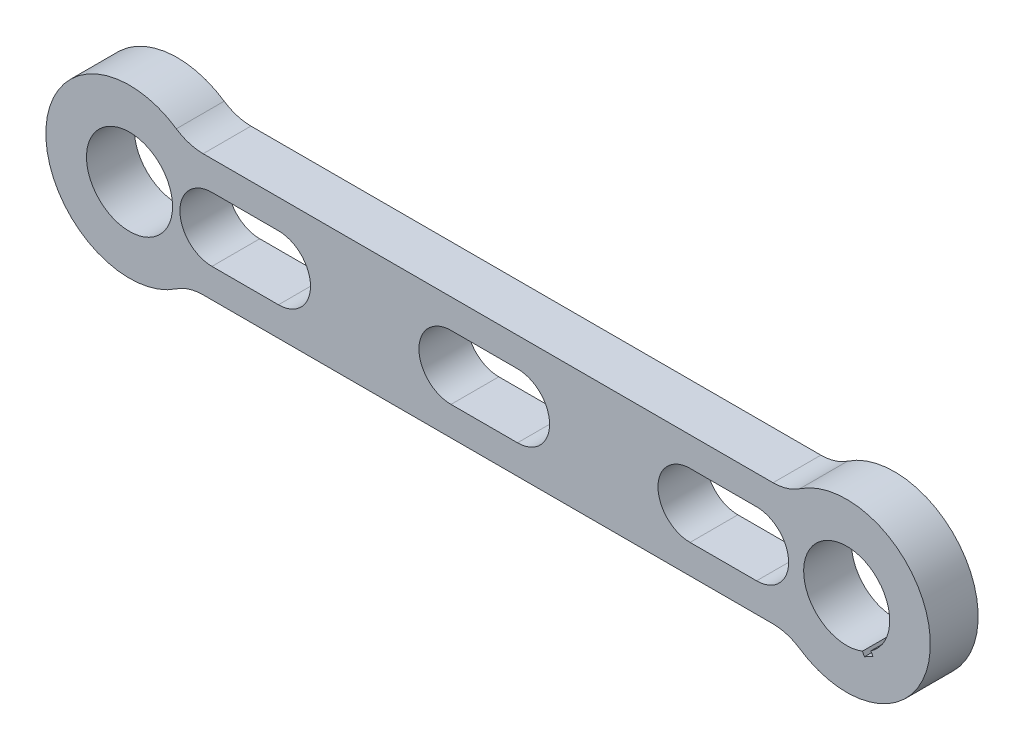
SolidWorks part; units mm, degrees
ref_plane "Front Plane" through (0, 0, 0) normal (0, 0, 1) x (1, 0, 0)
ref_plane "Top Plane" through (0, 0, 0) normal (0, 1, 0) x (1, 0, 0)
ref_plane "Right Plane" through (0, 0, 0) normal (1, 0, 0) x (0, 0, -1)
sketch "Sketch1" plane through (0, 0, 0) normal (0, 0, 1) x (1, 0, 0)
  line L0 (-70.6553, 0) -> (79.3447, 0) construction
  line L1 (55, 0) -> (-55, 0) construction
  line L2 (-53.413, 0) -> (-39.5014, 0) construction
  line L3 (-58.704, 12.7835) -> (67.3934, 12.7835)
  line L4 (-58.704, -12.7835) -> (67.3934, -12.7835)
  line L5 (-53.413, 6.7024) -> (-39.5014, 6.7024)
  line L6 (-53.413, -6.7024) -> (-39.5014, -6.7024)
  line L7 (-3.413, 0) -> (10.4986, 0) construction
  line L8 (-3.413, 6.7024) -> (10.4986, 6.7024)
  line L9 (-3.413, -6.7024) -> (10.4986, -6.7024)
  line L10 (46.587, 0) -> (60.4986, 0) construction
  line L11 (46.587, 6.7024) -> (60.4986, 6.7024)
  line L12 (46.587, -6.7024) -> (60.4986, -6.7024)
  arc A2 (-53.413, 6.7024) -> (-53.413, -6.7024) centre (-53.413, 0) ccw
  arc A3 (-39.5014, -6.7024) -> (-39.5014, 6.7024) centre (-39.5014, 0) ccw
  arc A4 (-3.413, 6.7024) -> (-3.413, -6.7024) centre (-3.413, 0) ccw
  arc A5 (10.4986, -6.7024) -> (10.4986, 6.7024) centre (10.4986, 0) ccw
  arc A6 (46.587, 6.7024) -> (46.587, -6.7024) centre (46.587, 0) ccw
  arc A7 (60.4986, -6.7024) -> (60.4986, 6.7024) centre (60.4986, 0) ccw
  arc A8 (-58.704, 12.7835) -> (-58.704, -12.7835) centre (-70.6553, 0) ccw
  arc A9 (67.3934, -12.7835) -> (67.3934, 12.7835) centre (79.3447, 0) ccw
  circle A10 centre (-70.6553, 0) radius 9
  circle A11 centre (79.3447, 0) radius 9
  point P7 (4.3447, 0)
  point P12 (-46.4572, 0)
  point P20 (3.5428, 0)
  point P27 (53.5428, 0)
  dimension "D2" = 18
  dimension "D1" = 3
extrude "Boss-Extrude3" add sketch "Sketch1" along normal blind 10
fillet "Fillet1" radius 10 4 edges at (67.3934, 12.7835, 5) (67.3934, -12.7835, 5) (-58.704, -12.7835, 5) (-58.704, 12.7835, 5)
sketch "Sketch4" plane through (0, 0, 10) normal (0, 0, 1) x (1, 0, 0)
  line L0 (82.1845, -7.5091) -> (82.6258, -8.3437) construction
  line L1 (84.3938, -7.4087) -> (83.9525, -6.5741) construction
  line L3 (82.6258, -8.3437) -> (83.0672, -9.1782)
  line L4 (84.8352, -8.2432) -> (84.3938, -7.4087)
  line L6 (84.3938, -7.4087) -> (82.6258, -8.3437)
  line L7 (84.8352, -8.2432) -> (83.0672, -9.1782)
extrude "Cut-Extrude2" cut sketch "Sketch4" against normal blind 10
